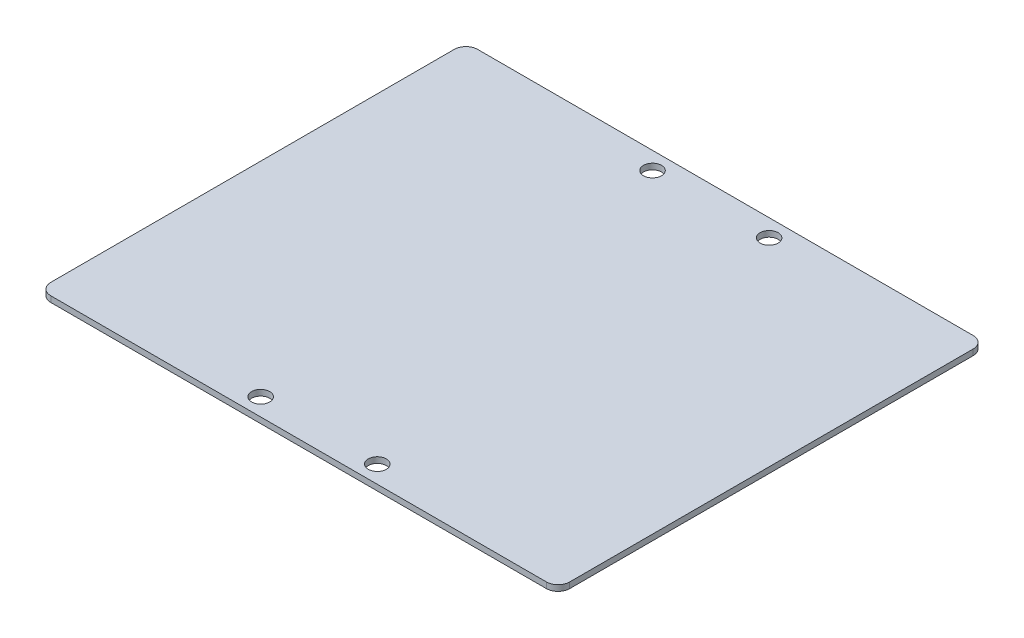
SolidWorks part; units mm, degrees
material "Thornel Mat VMA"
ref_plane "前视基准面" through (0, 0, 0) normal (0, 0, 1) x (1, 0, 0)
ref_plane "上视基准面" through (0, 0, 0) normal (0, 1, 0) x (1, 0, 0)
ref_plane "右视基准面" through (0, 0, 0) normal (1, 0, 0) x (0, 0, -1)
other "Configuration Table"
sketch "草图1" plane through (0, 0, 0) normal (0, 1, 0) x (1, 0, 0)
  line L1 (-44.5, 36.6) -> (44.5, 36.6)
  line L2 (-44.5, 36.6) -> (-44.5, -36.6)
  line L3 (-44.5, -36.6) -> (44.5, -36.6)
  line L4 (44.5, 36.6) -> (44.5, -36.6)
  line L5 (-44.5, 36.6) -> (44.5, -36.6) construction
  line L6 (-44.5, -36.6) -> (44.5, 36.6) construction
  point P0 (0, 0)
  dimension "D1" = 89
  dimension "D2" = 73.2
extrude "凸台-拉伸1" add sketch "草图1" along normal blind 1
sketch "草图2" plane through (0, 0, 0) normal (0, -1, 0) x (1, 0, 0)
  circle A0 centre (10.5, 33.6) radius 1.55
  circle A1 centre (-9.5, 33.6) radius 1.55
  circle A2 centre (-9.5, -33.6) radius 1.55
  circle A3 centre (10.5, -33.6) radius 1.55
  dimension "D1" = 3.1
extrude "切除-拉伸1" cut sketch "草图2" against normal blind 10
fillet "圆角1" radius 2 4 edges at (44.5, 0.5, 36.6) (-44.5, 0.5, 36.6) (-44.5, 0.5, -36.6) (44.5, 0.5, -36.6)
